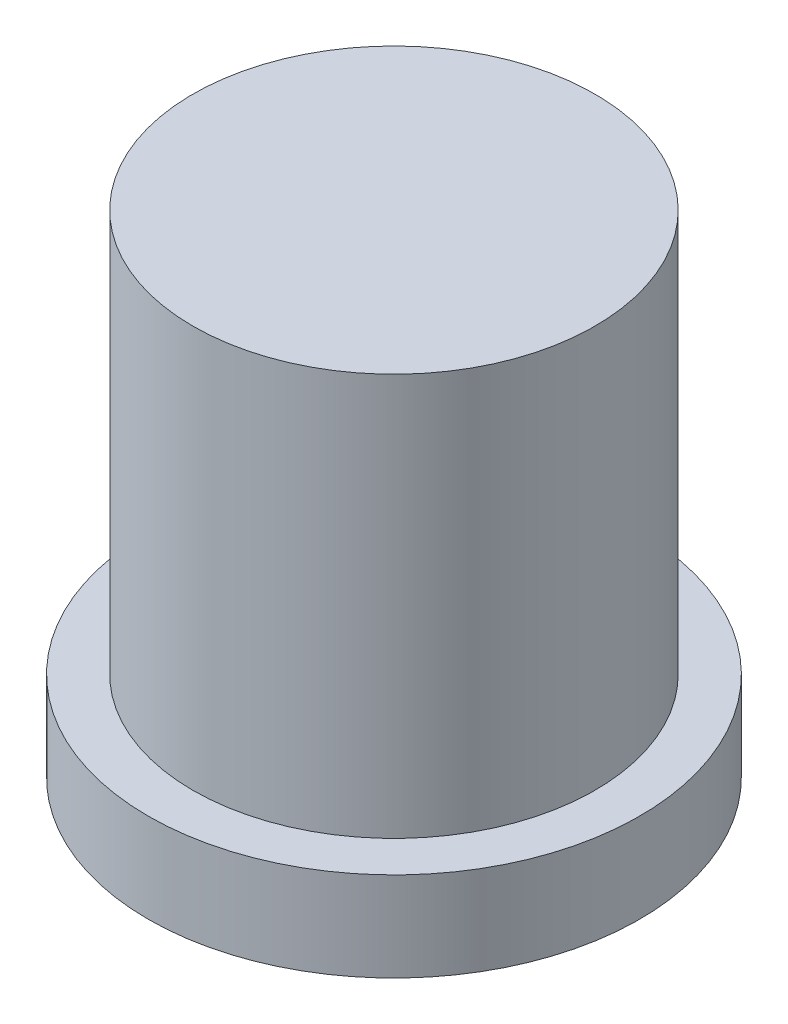
SolidWorks part; units mm, degrees
ref_plane "Front Plane" through (0, 0, 0) normal (0, 0, 1) x (1, 0, 0)
ref_plane "Top Plane" through (0, 0, 0) normal (0, 1, 0) x (1, 0, 0)
ref_plane "Right Plane" through (0, 0, 0) normal (1, 0, 0) x (0, 0, -1)
sketch "Sketch1" plane through (0, 0, 0) normal (0, 1, 0) x (1, 0, 0)
  circle A0 centre (0, 0) radius 34.925
extrude "Boss-Extrude1" add sketch "Sketch1" along normal blind 12.7
sketch "Sketch2" plane through (0, 12.7, 0) normal (0, 1, 0) x (1, 0, 0)
  circle A0 centre (0, 0) radius 28.575
extrude "Boss-Extrude2" add sketch "Sketch2" along normal blind 57.15
